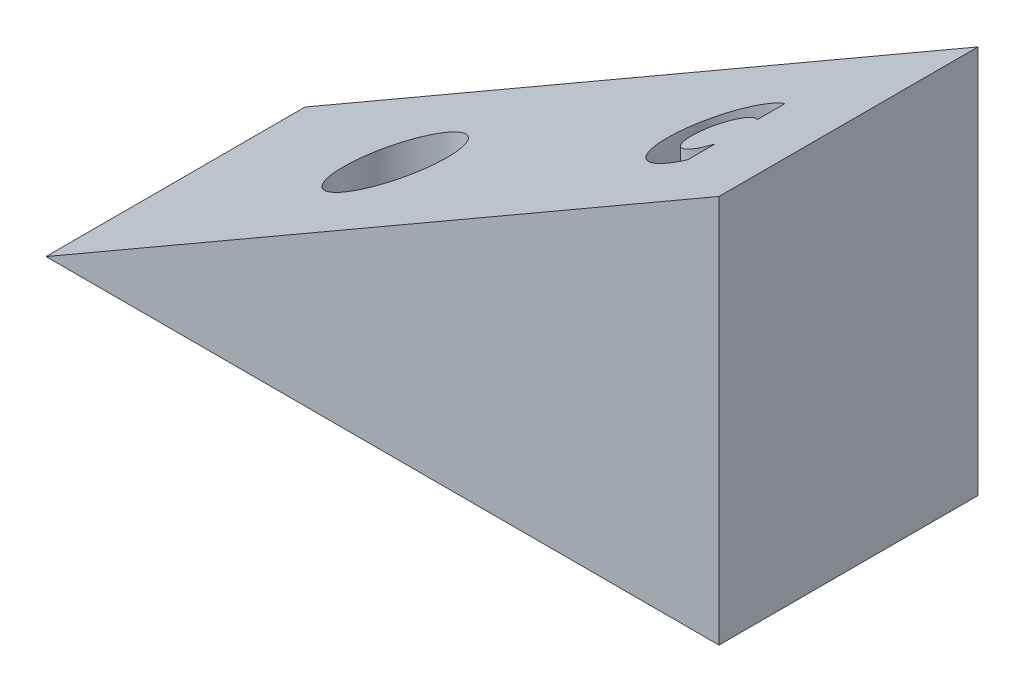
SolidWorks part; units mm, degrees
ref_plane "正面" through (0, 0, 0) normal (0, 0, 1) x (1, 0, 0)
ref_plane "平面" through (0, 0, 0) normal (0, 1, 0) x (1, 0, 0)
ref_plane "右側面" through (0, 0, 0) normal (1, 0, 0) x (0, 0, -1)
sketch "ｽｹｯﾁ1" plane through (0, 0, 0) normal (0, 0, 1) x (1, 0, 0)
  line L0 (0, 0) -> (51.9615, 0)
  line L1 (0, 0) -> (51.9615, 30)
  line L2 (51.9615, 30) -> (51.9615, 0)
  dimension "D1" = 60
  dimension "D2" = 30
extrude "ﾎﾞｽ - 押し出し1" add sketch "ｽｹｯﾁ1" along normal blind 20
sketch "ｽｹｯﾁ2" plane through (0, 0, 0) normal (0, -1, 0) x (-1, 0, 0)
  line L0 (0, 0) -> (-51.9615, 0) construction
  line L2 (-51.9615, -20) -> (-51.9615, 0) construction
  circle A0 centre (-16.9615, -10) radius 2.1
  circle A1 centre (-41.9615, -10) radius 2.1
  dimension "D1" = 4.2
  dimension "D2" = 4.2
  dimension "D3" = 10
  dimension "D4" = 25
  dimension "D5" = 10
  dimension "D6" = 10
extrude "ｶｯﾄ - 押し出し1" cut sketch "ｽｹｯﾁ2" against normal blind 20
ref_plane "平面1" through (0, 5, 0) normal (0, -1, 0) x (-1, 0, 0)
sketch "ｽｹｯﾁ3" plane through (0, 5, 0) normal (0, -1, 0) x (-1, 0, 0)
  circle A0 centre (-41.9615, -10) radius 2.1 construction
  circle A1 centre (-16.9615, -10) radius 2.1 construction
  circle A2 centre (-41.9615, -10) radius 2.1
  circle A3 centre (-16.9615, -10) radius 2.1
  circle A4 centre (-16.9615, -10) radius 4
  circle A5 centre (-41.9615, -10) radius 4
  dimension "D1" = 8
  dimension "D2" = 8
extrude "ｶｯﾄ - 押し出し2" cut sketch "ｽｹｯﾁ3" against normal blind 20
